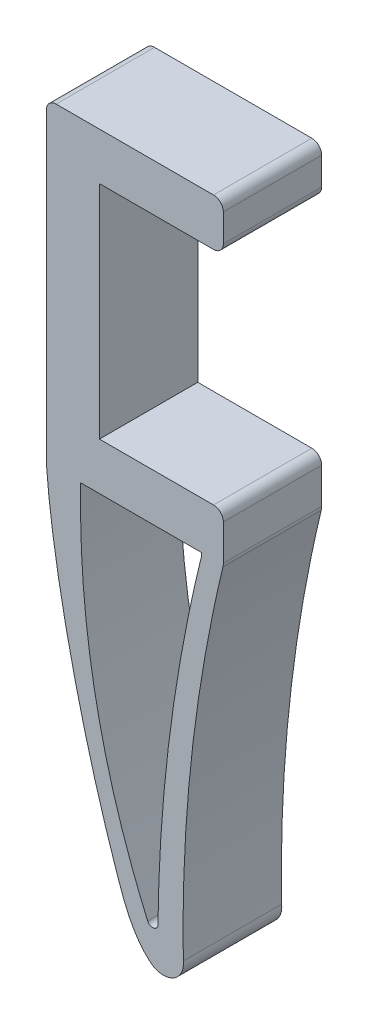
SolidWorks part; units mm, degrees
ref_plane "前视基准面" through (0, 0, 0) normal (0, 0, 1) x (1, 0, 0)
ref_plane "上视基准面" through (0, 0, 0) normal (0, 1, 0) x (1, 0, 0)
ref_plane "右视基准面" through (0, 0, 0) normal (1, 0, 0) x (0, 0, -1)
sketch "草图1" plane through (0, 0, 0) normal (0, 0, 1) x (1, 0, 0)
  line L0 (-1, 0) -> (-17, 0)
  line L1 (-18, -1) -> (-18, -32.1)
  line L5 (0, -31.9225) -> (0, -27.3)
  line L6 (0, -27.3) -> (-12.6, -27.3)
  line L7 (-12.6, -27.3) -> (-12.6, -4.8)
  line L8 (-12.6, -4.8) -> (0, -4.8)
  line L9 (0, -4.8) -> (0, -1)
  line L10 (-14.5029, -32.1) -> (-2.2016, -32.1)
  line L11 (-2.2016, -32.1) -> (-2.2016, -32.344)
  line L12 (0, -27.3) -> (0, -19.6342) construction
  arc A0 (-7.4064, -70.7881) -> (-4.0699, -69.0041) centre (-6.0936, -69.2314) ccw
  arc A3 (-7.6957, -67.2871) -> (-6.6465, -66.9904) centre (-7.1913, -67.0673) ccw
  arc A4 (0, -1) -> (-1, 0) centre (-1, -1) ccw
  arc A5 (-18, -1) -> (-17, 0) centre (-17, -1) cw
  arc A6 (0, -31.9225) -> (-0.0412, -32.2718) centre (-1.5, -31.9225) cw
  spline S0 degree 3 poles (-18, -32.1) (-17.399, -40.62) (-14.024, -56.3643) (-9.1468, -69.3203) (-7.4064, -70.7881) knots 0 0 0 0 0.832204 1 1 1 1
  spline S1 degree 3 poles (-0.0412, -32.2718) (-1.5, -38.3638) (-3.6302, -50.5779) (-4.1858, -62.852) (-4.0699, -69.0041) knots 0.004176 0.004176 0.004176 0.004176 0.448416 0.892657 0.892657 0.892657 0.892657
  spline S2 degree 3 poles (-14.5029, -32.1) (-14.7535, -44.5732) (-12.4844, -56.3023) (-7.6957, -67.2871) knots 0 0 0 0 1 1 1 1
  spline S3 degree 2 poles (-2.2016, -32.344) (-6.4406, -49.5395) (-6.6465, -66.9904) knots 0 0 0 0.915734 0.915734 0.915734
  point P19 (0, 0)
  point P23 (-18, 0)
  dimension "D6" = 69.2314
  dimension "D7" = 1
  dimension "D3" = 1.5
  dimension "D1" = 22.5
  dimension "D2" = 4.8
  dimension "D4" = 18
  dimension "D5" = 12.6
extrude "凸台-拉伸1" add sketch "草图1" along normal blind 10
fillet "圆角2" radius 1 2 edges at (0, -27.3, 5) (0, -4.8, 5)
